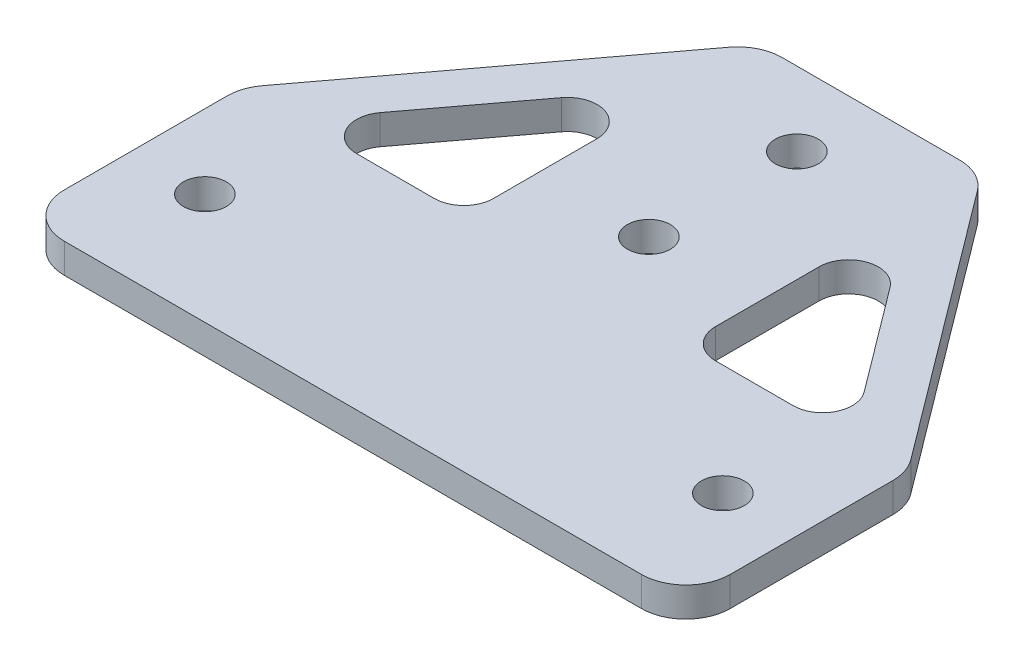
SolidWorks part; units mm, degrees
material "Thornel Mat VMA"
ref_plane "前视基准面" through (0, 0, 0) normal (0, 0, 1) x (1, 0, 0)
ref_plane "上视基准面" through (0, 0, 0) normal (0, 1, 0) x (1, 0, 0)
ref_plane "右视基准面" through (0, 0, 0) normal (1, 0, 0) x (0, 0, -1)
other "Configuration Table"
sketch "草图1" plane through (0, 0, 0) normal (0, 1, 0) x (1, 0, 0)
  line L0 (-7.5, 27.5) -> (-22.5, 7.5)
  line L1 (-22.5, -7.5) -> (22.5, -7.5) construction
  line L2 (-22.5, -7.5) -> (-22.5, 7.5) construction
  line L3 (-22.5, 7.5) -> (22.5, 7.5) construction
  line L4 (22.5, -7.5) -> (22.5, 7.5) construction
  line L5 (-22.5, -7.5) -> (22.5, 7.5) construction
  line L6 (-22.5, 7.5) -> (22.5, -7.5) construction
  line L7 (-7.5, -7.5) -> (7.5, -7.5) construction
  line L8 (-7.5, -7.5) -> (-7.5, 27.5) construction
  line L9 (-7.5, 27.5) -> (7.5, 27.5) construction
  line L10 (7.5, -7.5) -> (7.5, 27.5) construction
  line L11 (-22.5, 7.5) -> (-22.5, -7.5)
  line L12 (-22.5, -7.5) -> (22.5, -7.5)
  line L13 (22.5, -7.5) -> (22.5, 7.5)
  line L14 (22.5, 7.5) -> (7.5, 27.5)
  line L15 (7.5, 27.5) -> (-7.5, 27.5)
  line L16 (0, 39.9087) -> (0, -31.2831) construction
  line L17 (-34.6801, 0) -> (35.4753, 0) construction
  line L18 (-7.5, 22.5) -> (-18.75, 7.5)
  line L19 (-18.75, 7.5) -> (-7.5, 7.5)
  line L20 (-7.5, 7.5) -> (-7.5, 22.5)
  line L21 (18.75, 7.5) -> (7.5, 7.5)
  line L22 (7.5, 7.5) -> (7.5, 22.5)
  line L23 (7.5, 22.5) -> (18.75, 7.5)
  circle A0 centre (-17.5, 0) radius 1.45
  circle A1 centre (17.5, 0) radius 1.45
  circle A2 centre (0, 12.5) radius 1.45
  circle A3 centre (0, 22.5) radius 1.45
  point P0 (0, 0)
  dimension "D1" = 5
  dimension "D2" = 10
  dimension "D3" = 5
  dimension "D7" = 17.5
  dimension "D9" = 5
  dimension "D10" = 2.9
  dimension "D4" = 7.5
  dimension "D5" = 7.5
  dimension "D6" = 15
  dimension "D8" = 17.5
  dimension "D11" = 3
extrude "凸台-拉伸1" add sketch "草图1" along normal blind 2
fillet "圆角2" radius 3 6 edges at (22.5, 1, -7.5) (22.5, 1, 7.5) (-22.5, 1, 7.5) (-22.5, 1, -7.5) (-7.5, 1, -27.5) (7.5, 1, -27.5)
fillet "圆角3" radius 2 6 edges at (-7.5, 1, -7.5) (-18.75, 1, -7.5) (-7.5, 1, -22.5) (7.5, 1, -7.5) (18.75, 1, -7.5) (7.5, 1, -22.5)
